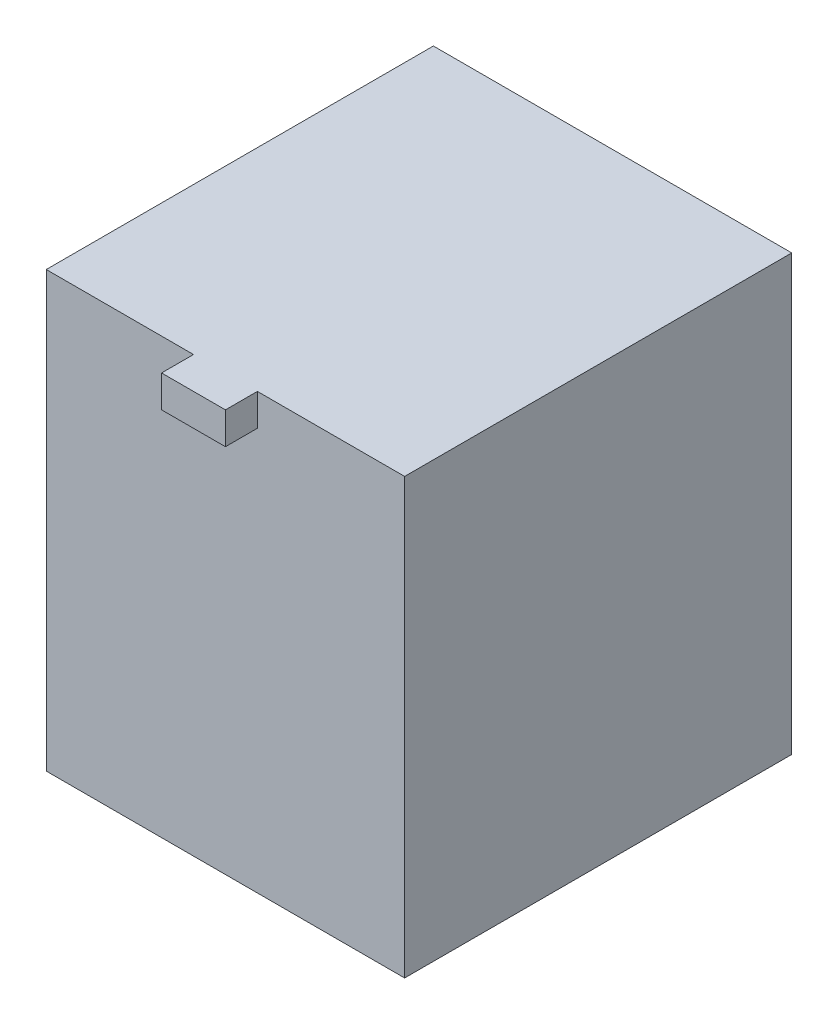
SolidWorks part; units mm, degrees
ref_plane "前视基准面" through (0, 0, 0) normal (0, 0, 1) x (1, 0, 0)
ref_plane "上视基准面" through (0, 0, 0) normal (0, 1, 0) x (1, 0, 0)
ref_plane "右视基准面" through (0, 0, 0) normal (1, 0, 0) x (0, 0, -1)
other "Configuration Table"
sketch "草图1" plane through (0, 0, 0) normal (0, 1, 0) x (1, 0, 0)
  line L1 (-28.05, -30.3) -> (28.05, -30.3)
  line L2 (-28.05, -30.3) -> (-28.05, 30.3)
  line L3 (-28.05, 30.3) -> (28.05, 30.3)
  line L4 (28.05, -30.3) -> (28.05, 30.3)
  line L5 (-28.05, -30.3) -> (28.05, 30.3) construction
  line L6 (-28.05, 30.3) -> (28.05, -30.3) construction
  point P0 (0, 0)
  dimension "D1" = 56.1
  dimension "D2" = 60.6
extrude "凸台-拉伸1" add sketch "草图1" along normal blind 68
sketch "草图2" plane through (0, 0, 30.3) normal (0, 0, 1) x (1, 0, 0)
  line L0 (-5, 68) -> (5, 68)
  line L1 (-28.05, 68) -> (28.05, 68) construction
  line L2 (5, 68) -> (5, 63)
  line L3 (5, 63) -> (-5, 63)
  line L4 (0, 63) -> (0, 68)
  line L5 (0, 0) -> (0, 79.1242) construction
  line L6 (-5, 68) -> (-5, 63)
  line M8 (28.05, 68) -> (-28.05, 68)
  dimension "D1" = 5
  dimension "D2" = 5
extrude "凸台-拉伸2" add sketch "草图2" along normal blind 5 contours L0 L6 L3 L4 | L4 L3 L2 M8
